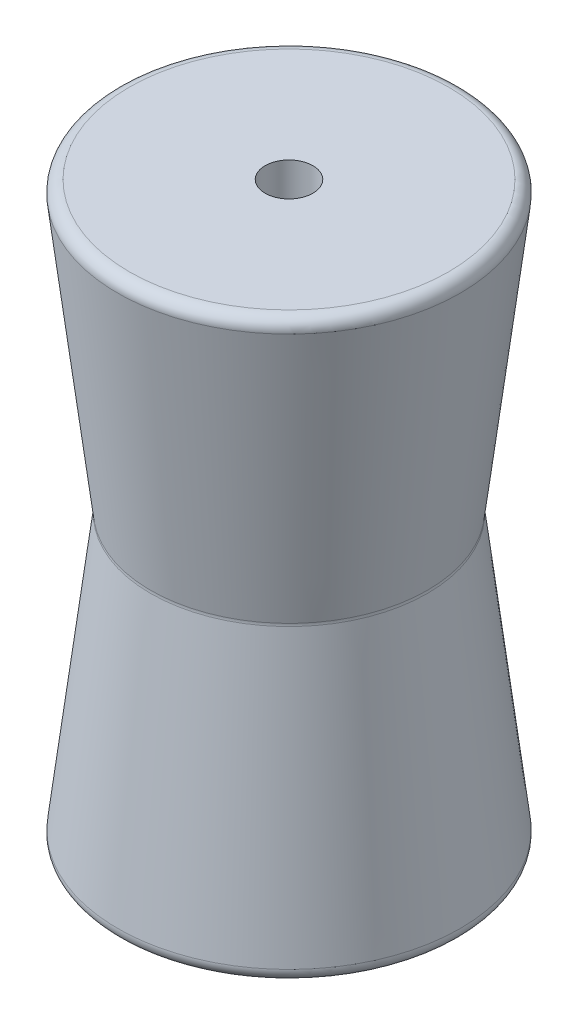
SolidWorks part; units mm, degrees
ref_plane "前视基准面" through (0, 0, 0) normal (0, 0, 1) x (1, 0, 0)
ref_plane "上视基准面" through (0, 0, 0) normal (0, 1, 0) x (1, 0, 0)
ref_plane "右视基准面" through (0, 0, 0) normal (1, 0, 0) x (0, 0, -1)
other "Configuration Table"
sketch "草图2" plane through (0, 0, 0) normal (0, 0, 1) x (1, 0, 0)
  line L0 (0, 0) -> (0, 50)
  line L1 (0, 25) -> (-12, 25) construction
  line L2 (-12, 25) -> (-15, 0)
  line L3 (-15, 0) -> (0, 0)
  line L4 (-12, 25) -> (-15, 50)
  line L5 (-15, 50) -> (0, 50)
  dimension "D1" = 15
  dimension "D2" = 12
  dimension "D3" = 25
revolve "旋转1" add sketch "草图2" angle 360 about L0
sketch "草图3" plane through (0, 0, 0) normal (0, -1, 0) x (1, 0, 0)
  circle A0 centre (0, 0) radius 2.075
  dimension "D1" = 4.15
extrude "切除-拉伸1" cut sketch "草图3" against normal blind 60
fillet "圆角1" radius 1 3 edges at (15, 0, 0) (12, 25, 0) (15, 50, 0)
